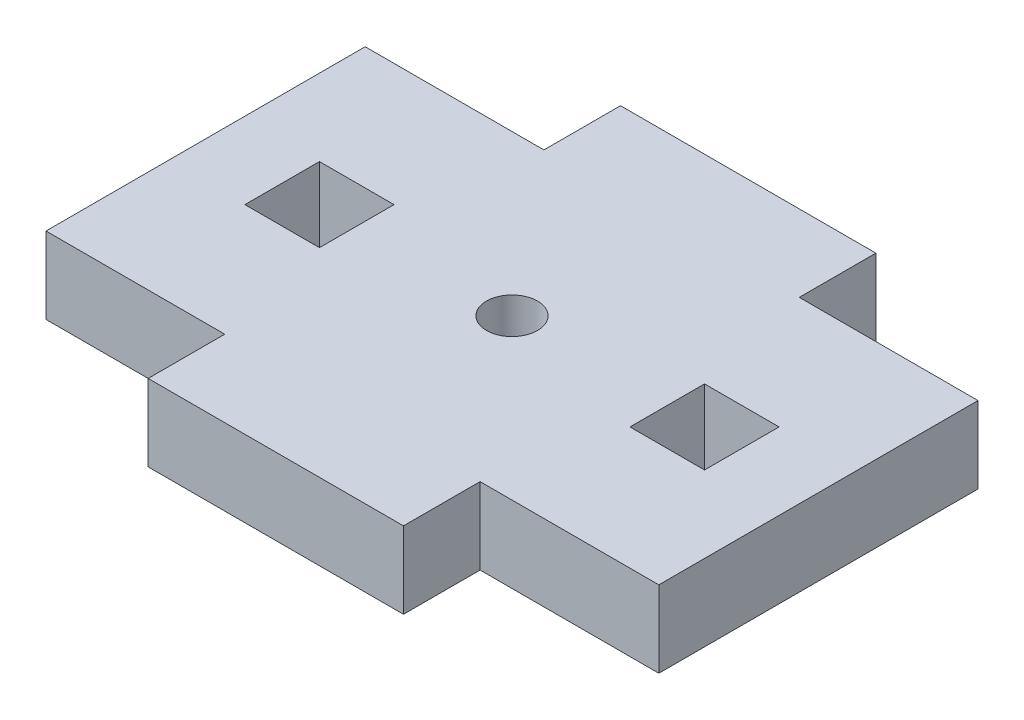
SolidWorks part; units mm, degrees
ref_plane "Front Plane" through (0, 0, 0) normal (0, 0, 1) x (1, 0, 0)
ref_plane "Top Plane" through (0, 0, 0) normal (0, 1, 0) x (1, 0, 0)
ref_plane "Right Plane" through (0, 0, 0) normal (1, 0, 0) x (0, 0, -1)
sketch "Sketch1" plane through (0, 0, 0) normal (0, 1, 0) x (1, 0, 0)
  line L0 (2.901, 5.142) -> (2.901, 8.142)
  line L1 (-14.099, 5.142) -> (9.901, 5.142)
  line L2 (-14.099, 5.142) -> (-14.099, -7.358)
  line L3 (-14.099, -7.358) -> (9.901, -7.358)
  line L4 (9.901, 5.142) -> (9.901, -7.358)
  line L5 (2.901, 8.142) -> (-7.099, 8.142)
  line L6 (-7.099, 8.142) -> (-7.099, 5.142)
  line L7 (-14.099, -1.108) -> (9.901, -1.108) construction
  line L8 (-7.099, -10.358) -> (-7.099, -7.358)
  line L9 (2.901, -7.358) -> (2.901, -10.358)
  line L10 (2.901, -10.358) -> (-7.099, -10.358)
  line L12 (3.981, 0.352) -> (6.901, 0.352)
  line L13 (3.981, 0.352) -> (3.981, -2.568)
  line L14 (3.981, -2.568) -> (6.901, -2.568)
  line L15 (6.901, 0.352) -> (6.901, -2.568)
  line L16 (-11.099, 0.352) -> (-8.179, 0.352)
  line L17 (-11.099, 0.352) -> (-11.099, -2.568)
  line L18 (-11.099, -2.568) -> (-8.179, -2.568)
  line L19 (-8.179, 0.352) -> (-8.179, -2.568)
  circle A0 centre (-2.099, -1.108) radius 1
  dimension "D7" = 2
  dimension "D8" = 12
  dimension "D9" = 6.25
  dimension "D1" = 12.5
  dimension "D2" = 24
  dimension "D3" = 3
  dimension "D4" = 10
  dimension "D5" = 7
  dimension "D6" = 7
  dimension "D10" = 2.92
  dimension "D11" = 2.92
  dimension "D12" = 3
  dimension "D13" = 4.79
  dimension "D14" = 2.92
  dimension "D15" = 2.92
  dimension "D16" = 4.79
  dimension "D17" = 3
extrude "Boss-Extrude1" add sketch "Sketch1" along normal blind 3 contours L7 L2 L3 L4 L15 L14 L13 A0 L19 L18 L17 | L2 L7 L17 L16 L19 A0 L13 L12 L15 L4 L1 | L5 L6 L1 L0 | L10 L9 L3 L8
